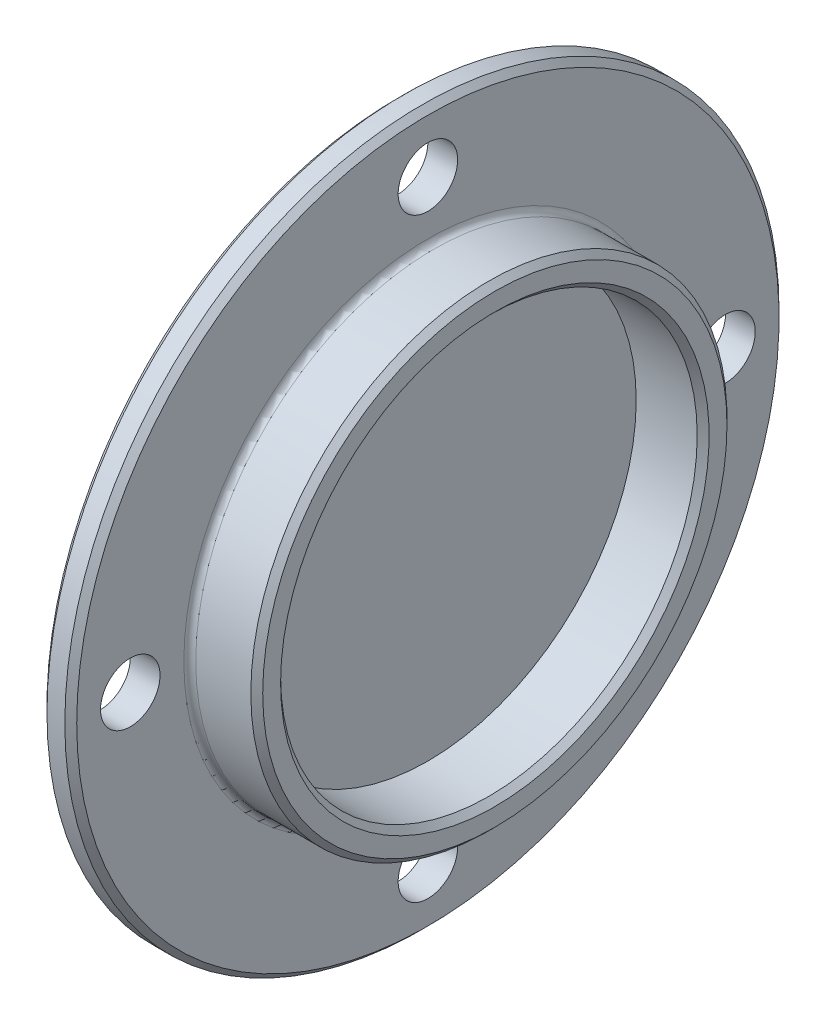
SolidWorks part; units mm, degrees
ref_plane "前视基准面" through (0, 0, 0) normal (0, 0, 1) x (1, 0, 0)
ref_plane "上视基准面" through (0, 0, 0) normal (0, 1, 0) x (1, 0, 0)
ref_plane "右视基准面" through (0, 0, 0) normal (1, 0, 0) x (0, 0, -1)
other "Configuration Table"
sketch "草图1" plane through (0, 0, 0) normal (0, 0, 1) x (1, 0, 0)
  line L0 (-39.7802, 0) -> (41.5385, 0) construction
  line L1 (0, 0) -> (10, 0)
  line L2 (10, 0) -> (10, 70)
  line L3 (10, 70) -> (32.5, 70)
  line L4 (32.5, 70) -> (32.5, 80)
  line L5 (32.5, 80) -> (10, 80)
  line L6 (10, 80) -> (10, 120)
  line L7 (10, 120) -> (0, 120)
  line L8 (0, 120) -> (0, 0)
  dimension "D1" = 10
  dimension "D2" = 120
  dimension "D3" = 70
  dimension "D4" = 80
  dimension "D5" = 22.5
revolve "旋转1" add sketch "草图1" angle 360 about L0
sketch "草图2" plane through (0, 0, 0) normal (1, 0, 0) x (0, 0, -1)
  line L0 (-180.0251, 0) -> (191.4033, 0) construction
  circle A0 centre (0, 0) radius 100 construction
  circle A1 centre (100, 0) radius 10
  circle A2 centre (0, -100) radius 10
  circle A3 centre (-100, 0) radius 10
  circle A4 centre (0, 100) radius 10
  point P16 (0, 0)
  dimension "D1" = 200
  dimension "D2" = 20
  dimension "D3" = 4
extrude "切除-拉伸3" cut sketch "草图2" along normal through all both
fillet "圆角1" radius 2 1 edges at (10, 0, 80)
chamfer "倒角1" distance 2 angle 45 4 edges at (0, 0, 120) (10, 0, 120) (32.5, 0, 70) (32.5, 0, 80)
